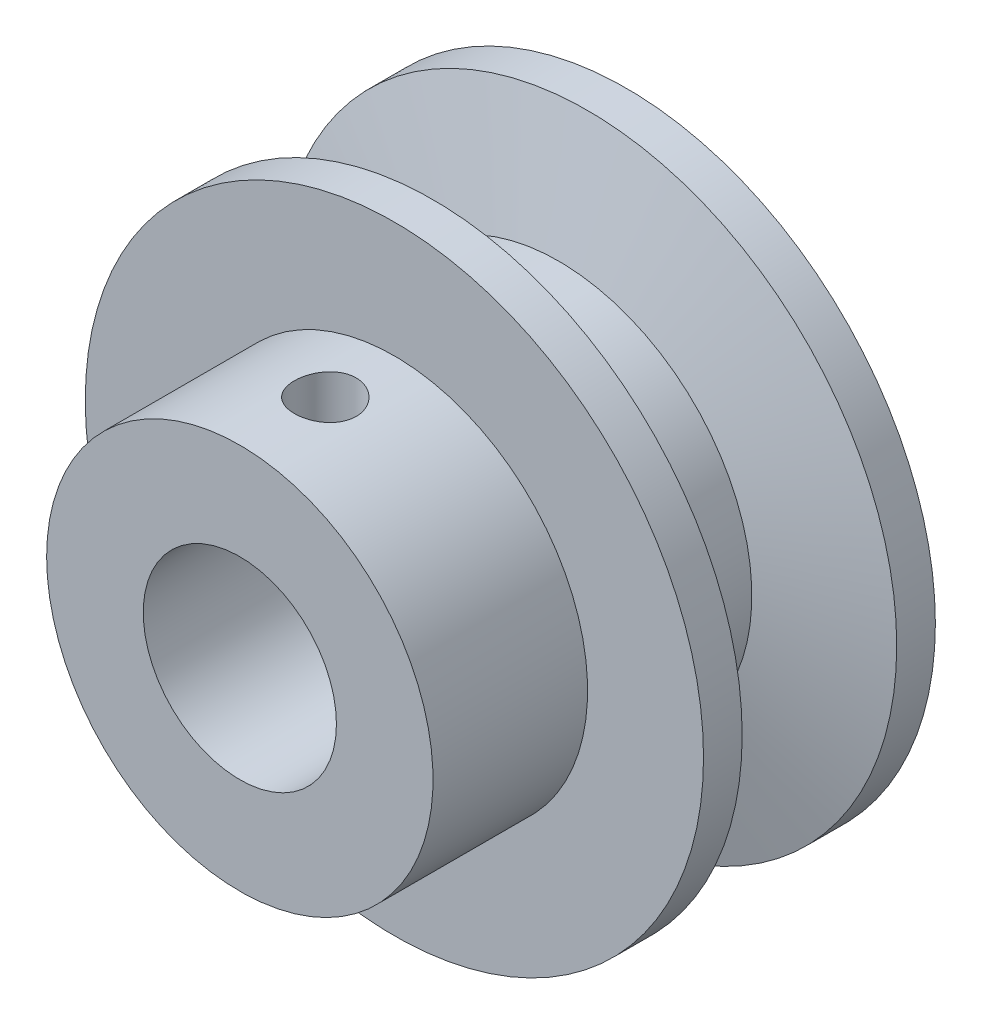
SolidWorks part; units mm, degrees
ref_plane "Front Plane" through (0, 0, 0) normal (0, 0, 1) x (1, 0, 0)
ref_plane "Top Plane" through (0, 0, 0) normal (0, 1, 0) x (1, 0, 0)
ref_plane "Right Plane" through (0, 0, 0) normal (1, 0, 0) x (0, 0, -1)
sketch "Sketch1" plane through (0, 0, 0) normal (0, 1, 0) x (1, 0, 0)
  line L2 (0, 24.3039) -> (40, 24.3039)
  line L3 (40, 24.3039) -> (40, 19.3039)
  line L6 (40, -0.6961) -> (40, -5.6961)
  line L7 (40, -5.6961) -> (25, -5.6961)
  line L8 (0, 24.3039) -> (0, -25.6961)
  line L9 (25, 3.0539) -> (25, 15.5539)
  line L10 (25, -5.6961) -> (25, -25.6961)
  line L11 (40, 19.3039) -> (25, 15.5539)
  line L12 (25, 3.0539) -> (40, -0.6961)
  line L13 (25, -25.6961) -> (0, -25.6961)
  dimension "D1" = 25
  dimension "D2" = 40
  dimension "D3" = 3.0539
  dimension "D4" = 15.5539
  dimension "D5" = 19.3039
  dimension "D6" = 24.3039
  dimension "D9" = 25.6961
revolve "Revolve1" add sketch "Sketch1" angle 360 about L8
sketch "Sketch2" plane through (0, 0, 25.6961) normal (0, 0, 1) x (1, 0, 0)
  circle A0 centre (0, 0) radius 12.5
  dimension "D1" = 25
extrude "Cut-Extrude1" cut sketch "Sketch2" against normal blind 70 contours A0
sketch "Sketch4" plane through (0, 0, 25.6961) normal (0, 0, 1) x (1, 0, 0)
  line L0 (0, 0) -> (25, 0)
  line L1 (0, 0) -> (0, 25)
  circle A0 centre (0, 0) radius 25 construction
  circle A1 centre (0, 0) radius 25 construction
  dimension "D1" = 90
ref_plane "Plane1" through (0, 25, 25.6961) normal (0, 1, 0) x (1, 0, 0)
sketch "Sketch5" plane through (0, 25, 25.6961) normal (0, 1, 0) x (1, 0, 0)
  circle A0 centre (0, 11.0583) radius 4
  dimension "D1" = 8
  dimension "D2" = 14.6378
extrude "Cut-Extrude2" cut sketch "Sketch5" against normal blind 27 contours A0
